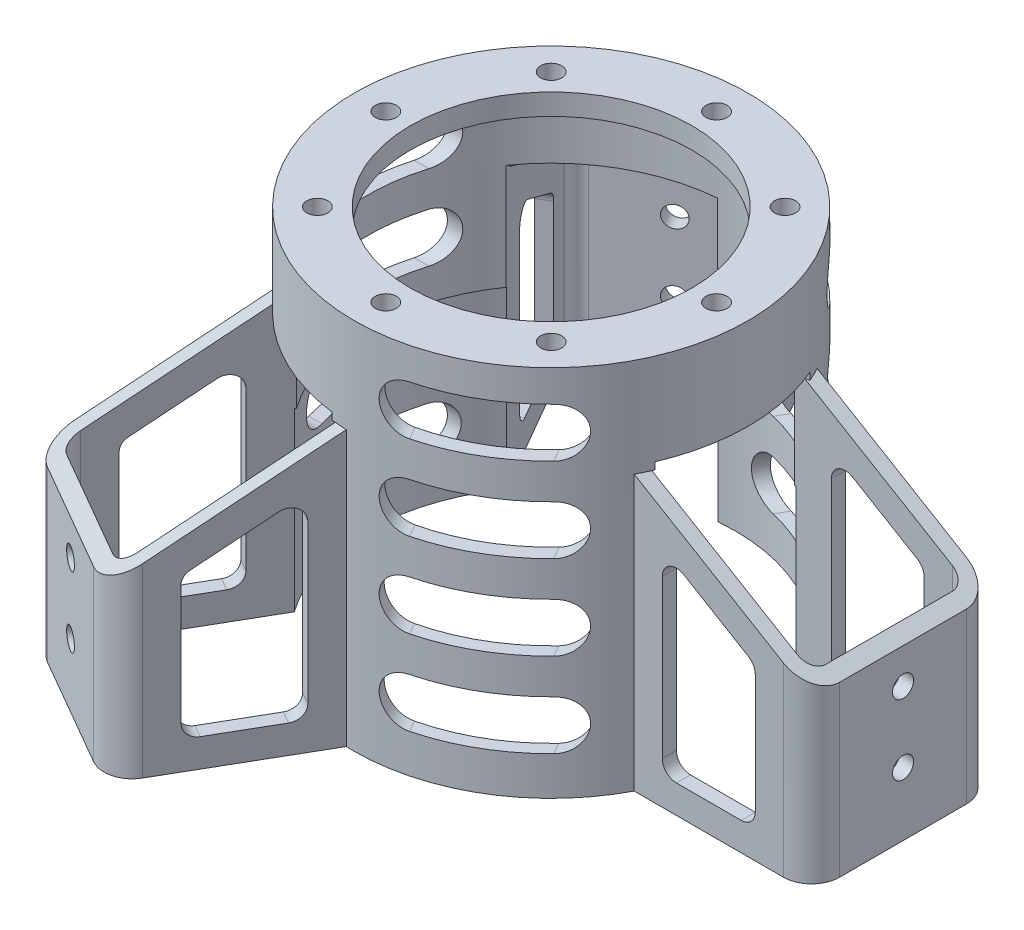
SolidWorks part; units mm, degrees
material "1060 合金"
ref_plane "前视基准面" through (0, 0, 0) normal (0, 0, 1) x (1, 0, 0)
ref_plane "上视基准面" through (0, 0, 0) normal (0, 1, 0) x (1, 0, 0)
ref_plane "右视基准面" through (0, 0, 0) normal (1, 0, 0) x (0, 0, -1)
other "Configuration Table"
sketch "草图1" plane through (0, 0, 0) normal (0, 0, 1) x (1, 0, 0)
  line L0 (0, 49.0609) -> (0, -25.2041) construction
  line L1 (26, 50) -> (26, 0)
  line L2 (26, 0) -> (28, 0)
  line L6 (28, 0) -> (28, 50)
  line L7 (28, 50) -> (26, 50)
  dimension "D1" = 26
  dimension "D3" = 50
  dimension "D7" = 2
revolve "旋转1" add sketch "草图1" angle 360 about L0
sketch "草图17" plane through (0, 50, 0) normal (0, 1, 0) x (1, 0, 0)
  circle A0 centre (0, 0) radius 20
  circle A1 centre (0, 0) radius 28
  circle A2 centre (0, 23.5) radius 1.5
  circle A3 centre (16.617, 16.617) radius 1.5
  circle A4 centre (23.5, 0) radius 1.5
  circle A5 centre (16.617, -16.617) radius 1.5
  circle A6 centre (0, -23.5) radius 1.5
  circle A7 centre (-16.617, -16.617) radius 1.5
  circle A8 centre (-23.5, 0) radius 1.5
  circle A9 centre (-16.617, 16.617) radius 1.5
  point P7 (0, 0)
  point P8 (-23.5, 0)
  point P22 (0, 0)
  point P24 (0, 0)
  dimension "D1" = 40
  dimension "D2" = 56
  dimension "D3" = 23.5
  dimension "D4" = 3
  dimension "D5" = 8
extrude "凸台-拉伸4" add sketch "草图17" along normal blind 3
sketch "草图10" plane through (0, 0, 0) normal (0, -1, 0) x (1, 0, 0)
  line L0 (-24.7992, 13) -> (-46, 13) construction
  line L1 (-50, 9) -> (-50, -9) construction
  line L2 (-46, -13) -> (-24.7992, -13) construction
  line L3 (-1.1413, 27.9767) -> (-11.7417, 46.3372)
  line L4 (-17.2058, 47.8013) -> (-32.7942, 38.8013)
  line L5 (-34.2583, 33.3372) -> (-23.6579, 14.9767)
  line L6 (23.6579, 14.9767) -> (34.2583, 33.3372) construction
  line L7 (32.7942, 38.8013) -> (17.2058, 47.8013) construction
  line L8 (11.7417, 46.3372) -> (1.1413, 27.9767) construction
  line L9 (24.7992, -13) -> (46, -13)
  line L10 (50, -9) -> (50, 9)
  line L11 (46, 13) -> (24.7992, 13)
  line L12 (1.1413, -27.9767) -> (11.7417, -46.3372) construction
  line L13 (17.2058, -47.8013) -> (32.7942, -38.8013) construction
  line L14 (34.2583, -33.3372) -> (23.6579, -14.9767) construction
  line L15 (-23.6579, -14.9767) -> (-34.2583, -33.3372)
  line L16 (-32.7942, -38.8013) -> (-17.2058, -47.8013)
  line L17 (-11.7417, -46.3372) -> (-1.1413, -27.9767)
  line L18 (-27.9106, 11) -> (-46, 11) construction
  line L19 (-48, 9) -> (-48, -9) construction
  line L20 (-46, -11) -> (-27.9106, -11) construction
  line L21 (-4.429, 29.6713) -> (-13.4737, 45.3372)
  line L22 (-16.2058, 46.0692) -> (-31.7942, 37.0692)
  line L23 (-32.5263, 34.3372) -> (-23.4816, 18.6713)
  line L24 (23.4816, 18.6713) -> (32.5263, 34.3372) construction
  line L25 (31.7942, 37.0692) -> (16.2058, 46.0692) construction
  line L26 (13.4737, 45.3372) -> (4.429, 29.6713) construction
  line L27 (27.9106, -11) -> (46, -11)
  line L28 (48, -9) -> (48, 9)
  line L29 (46, 11) -> (27.9106, 11)
  line L30 (4.429, -29.6713) -> (13.4737, -45.3372) construction
  line L31 (16.2058, -46.0692) -> (31.7942, -37.0692) construction
  line L32 (32.5263, -34.3372) -> (23.4816, -18.6713) construction
  line L33 (-23.4816, -18.6713) -> (-32.5263, -34.3372)
  line L34 (-31.7942, -37.0692) -> (-16.2058, -46.0692)
  line L35 (-13.4737, -45.3372) -> (-4.429, -29.6713)
  circle A0 centre (0, 0) radius 28 construction
  arc A1 (-24.7992, 13) -> (-24.7992, -13) centre (0, 0) ccw construction
  arc A2 (-50, -9) -> (-46, -13) centre (-46, -9) ccw construction
  arc A3 (-46, 13) -> (-50, 9) centre (-46, 9) ccw construction
  arc A4 (-1.1413, 27.9767) -> (-23.6579, 14.9767) centre (0, 0) ccw
  arc A5 (-32.7942, 38.8013) -> (-34.2583, 33.3372) centre (-30.7942, 35.3372) ccw
  arc A6 (-11.7417, 46.3372) -> (-17.2058, 47.8013) centre (-15.2058, 44.3372) ccw
  arc A7 (23.6579, 14.9767) -> (1.1413, 27.9767) centre (0, 0) ccw construction
  arc A8 (17.2058, 47.8013) -> (11.7417, 46.3372) centre (15.2058, 44.3372) ccw construction
  arc A9 (34.2583, 33.3372) -> (32.7942, 38.8013) centre (30.7942, 35.3372) ccw construction
  arc A13 (24.7992, -13) -> (24.7992, 13) centre (0, 0) ccw
  arc A14 (50, 9) -> (46, 13) centre (46, 9) ccw
  arc A15 (46, -13) -> (50, -9) centre (46, -9) ccw
  arc A16 (1.1413, -27.9767) -> (23.6579, -14.9767) centre (0, 0) ccw construction
  arc A17 (32.7942, -38.8013) -> (34.2583, -33.3372) centre (30.7942, -35.3372) ccw construction
  arc A18 (11.7417, -46.3372) -> (17.2058, -47.8013) centre (15.2058, -44.3372) ccw construction
  arc A19 (-23.6579, -14.9767) -> (-1.1413, -27.9767) centre (0, 0) ccw
  arc A20 (-17.2058, -47.8013) -> (-11.7417, -46.3372) centre (-15.2058, -44.3372) ccw
  arc A21 (-34.2583, -33.3372) -> (-32.7942, -38.8013) centre (-30.7942, -35.3372) ccw
  arc A26 (-46, 11) -> (-48, 9) centre (-46, 9) ccw construction
  arc A27 (-48, -9) -> (-46, -11) centre (-46, -9) ccw construction
  arc A28 (-27.9106, 11) -> (-27.9106, -11) centre (0, 0) ccw construction
  arc A29 (-13.4737, 45.3372) -> (-16.2058, 46.0692) centre (-15.2058, 44.3372) ccw
  arc A30 (-31.7942, 37.0692) -> (-32.5263, 34.3372) centre (-30.7942, 35.3372) ccw
  arc A31 (-4.429, 29.6713) -> (-23.4816, 18.6713) centre (0, 0) ccw
  arc A32 (32.5263, 34.3372) -> (31.7942, 37.0692) centre (30.7942, 35.3372) ccw construction
  arc A33 (16.2058, 46.0692) -> (13.4737, 45.3372) centre (15.2058, 44.3372) ccw construction
  arc A34 (23.4816, 18.6713) -> (4.429, 29.6713) centre (0, 0) ccw construction
  arc A35 (46, -11) -> (48, -9) centre (46, -9) ccw
  arc A36 (48, 9) -> (46, 11) centre (46, 9) ccw
  arc A37 (27.9106, -11) -> (27.9106, 11) centre (0, 0) ccw
  arc A38 (13.4737, -45.3372) -> (16.2058, -46.0692) centre (15.2058, -44.3372) ccw construction
  arc A39 (31.7942, -37.0692) -> (32.5263, -34.3372) centre (30.7942, -35.3372) ccw construction
  arc A40 (4.429, -29.6713) -> (23.4816, -18.6713) centre (0, 0) ccw construction
  arc A41 (-32.5263, -34.3372) -> (-31.7942, -37.0692) centre (-30.7942, -35.3372) ccw
  arc A42 (-16.2058, -46.0692) -> (-13.4737, -45.3372) centre (-15.2058, -44.3372) ccw
  arc A43 (-23.4816, -18.6713) -> (-4.429, -29.6713) centre (0, 0) ccw
  point P11 (-50, 13)
  point P29 (0, 0)
  point P36 (0, 0)
  point P105 (0, 0)
  dimension "D4" = 4
  dimension "D6" = 2
  dimension "D7" = 6
  dimension "D1" = 13
  dimension "D2" = 26
  dimension "D3" = 50
  dimension "D5" = 6
extrude "凸台-拉伸2" add sketch "草图10" against normal blind 39
sketch "草图11" plane through (0, 0, 0) normal (0, 1, 0) x (1, 0, 0)
  line L0 (-25.4328, -22.0509) -> (-18.7219, -10.4273)
  line L5 (-32.5263, -34.3372) -> (-23.4816, -18.6713) construction
  line L6 (-18.7219, -10.4273) -> (0.3307, -21.4273)
  line L7 (-25.4328, -22.0509) -> (-6.3803, -33.0509)
  line L8 (-4.429, -29.6713) -> (-13.4737, -45.3372) construction
  line L9 (-6.3803, -33.0509) -> (0.3307, -21.4273)
  line L10 (-6.3803, 33.0509) -> (-25.4328, 22.0509)
  line L11 (-6.3803, 33.0509) -> (0.3307, 21.4273)
  line L12 (-25.4328, 22.0509) -> (-18.7219, 10.4273)
  line L13 (0.3307, 21.4273) -> (-18.7219, 10.4273)
  line L14 (31.8131, -11) -> (31.8131, 11)
  line L15 (31.8131, -11) -> (18.3912, -11)
  line L16 (31.8131, 11) -> (18.3912, 11)
  line L17 (18.3912, -11) -> (18.3912, 11)
  line L18 (-23.4816, 18.6713) -> (-32.5263, 34.3372) construction
  point P18 (0, 0)
  dimension "D1" = 3
extrude "切除-拉伸6" cut sketch "草图11" along normal blind 40
sketch "草图13" plane through (-25, 0, -43.3013) normal (-0.5, 0, -0.866) x (-0.866, 0, 0.5)
  line L0 (9, 39) -> (-9, 39) construction
  circle A0 centre (0, 19) radius 1.5
  circle A1 centre (0, 9) radius 1.5
  dimension "D1" = 20
  dimension "D2" = 3
  dimension "D3" = 2
extrude "切除-拉伸8" cut sketch "草图13" against normal blind 10
pattern_circular "阵列(圆周)3" count 3 over 360 about axis through (0, 53, 0) along (0, 1, 0) of "切除-拉伸8"
sketch "草图18" plane through (0, 0, 13) normal (0, 0, 1) x (1, 0, 0)
  line L0 (24.7992, 39) -> (50, 24)
  line L1 (50, 39) -> (50, 0) construction
  line L2 (50, 24) -> (50, 39)
  line L3 (50, 39) -> (24.7992, 39)
  dimension "D1" = 15
extrude "切除-拉伸11" cut sketch "草图18" against normal blind 40
pattern_circular "阵列(圆周)4" count 3 over 360 about axis through (0, 0, 0) along (0, 1, 0) of "切除-拉伸11"
sketch "草图15" plane through (0, 0, 0) normal (0, -1, 0) x (1, 0, 0)
  circle A0 centre (0, 0) radius 26.2
  arc A1 (-21.3055, 14.9022) -> (-21.3055, -14.9022) centre (0, 0) ccw construction
  dimension "D1" = 0.2
extrude "切除-拉伸10" cut sketch "草图15" against normal blind 25
sketch "草图19" plane through (0, 0, 0) normal (1, 0, 0) x (0, 0, -1)
  line L0 (7.5, 45) -> (-7.5, 45) construction
  line L1 (7.5, 41.5) -> (-7.5, 41.5)
  line L2 (7.5, 48.5) -> (-7.5, 48.5)
  line L3 (-14.9767, 0) -> (14.9767, 0) construction
  line L4 (7.5, 33) -> (-7.5, 33) construction
  line L5 (7.5, 29.5) -> (-7.5, 29.5)
  line L6 (7.5, 36.5) -> (-7.5, 36.5)
  line L7 (7.5, 21) -> (-7.5, 21) construction
  line L8 (7.5, 17.5) -> (-7.5, 17.5)
  line L9 (7.5, 24.5) -> (-7.5, 24.5)
  line L10 (7.5, 9) -> (-7.5, 9) construction
  line L11 (7.5, 5.5) -> (-7.5, 5.5)
  line L12 (7.5, 12.5) -> (-7.5, 12.5)
  arc A0 (7.5, 41.5) -> (7.5, 48.5) centre (7.5, 45) ccw
  arc A1 (-7.5, 48.5) -> (-7.5, 41.5) centre (-7.5, 45) ccw
  arc A2 (7.5, 29.5) -> (7.5, 36.5) centre (7.5, 33) ccw
  arc A3 (-7.5, 36.5) -> (-7.5, 29.5) centre (-7.5, 33) ccw
  arc A4 (7.5, 17.5) -> (7.5, 24.5) centre (7.5, 21) ccw
  arc A5 (-7.5, 24.5) -> (-7.5, 17.5) centre (-7.5, 21) ccw
  arc A6 (7.5, 5.5) -> (7.5, 12.5) centre (7.5, 9) ccw
  arc A7 (-7.5, 12.5) -> (-7.5, 5.5) centre (-7.5, 9) ccw
  point P2 (0, 45)
  point P13 (0, 33)
  point P20 (0, 21)
  point P27 (0, 9)
  dimension "D1" = 15
  dimension "D2" = 45
  dimension "D3" = 7
  dimension "D4" = 4
extrude "切除-拉伸12" cut sketch "草图19" against normal blind 40
pattern_circular "阵列(圆周)5" count 3 over 360 of "切除-拉伸12"
sketch "草图20" plane through (0, 0, -13) normal (0, 0, -1) x (-1, 0, 0)
  line L0 (-41.0229, 24.6884) -> (-31.8221, 30.1649)
  line L1 (-28.7992, 28.4463) -> (-28.7992, 6)
  line L2 (-30.7992, 4) -> (-40, 4)
  line L3 (-42, 6) -> (-42, 22.9698)
  line L4 (-46, 26.3809) -> (-24.7992, 39) construction
  line L5 (-46, 26.3809) -> (-46, 0) construction
  line L6 (-24.7992, 39) -> (-24.7992, 0) construction
  line L7 (-24.7992, 0) -> (-46, 0) construction
  arc A0 (-28.7992, 6) -> (-30.7992, 4) centre (-30.7992, 6) cw
  arc A1 (-31.8221, 30.1649) -> (-28.7992, 28.4463) centre (-30.7992, 28.4463) cw
  arc A2 (-42, 22.9698) -> (-41.0229, 24.6884) centre (-40, 22.9698) cw
  arc A3 (-40, 4) -> (-42, 6) centre (-40, 6) cw
  point P2 (-42.7933, 21.8033)
  dimension "D5" = 2
  dimension "D1" = 4
  dimension "D2" = 4
  dimension "D3" = 4
  dimension "D4" = 4
extrude "切除-拉伸13" cut sketch "草图20" against normal blind 40
pattern_circular "阵列(圆周)6" count 3 over 360 about axis through (0, 0, 0) along (0, 1, 0) of "切除-拉伸13"
